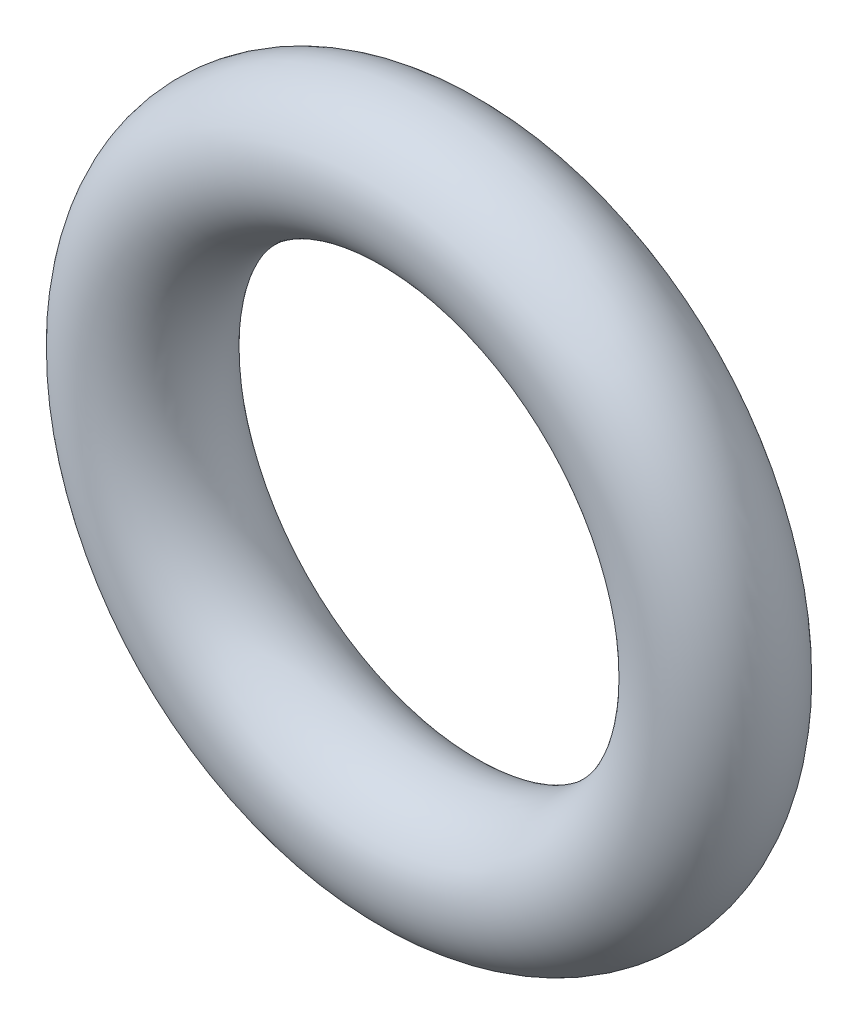
SolidWorks part; units mm, degrees
ref_plane "Front Plane" through (0, 0, 0) normal (0, 0, 1) x (1, 0, 0)
ref_plane "Top Plane" through (0, 0, 0) normal (0, 1, 0) x (1, 0, 0)
ref_plane "Right Plane" through (0, 0, 0) normal (1, 0, 0) x (0, 0, -1)
sketch "Sketch1" plane through (0, 0, 0) normal (0, 0, 1) x (1, 0, 0)
  circle A0 centre (0, 0) radius 2.1
  dimension "D1" = 4.2
sweep "Sweep1" add path "Sketch1" circular profile diameter 1 parameters "D3"=1
